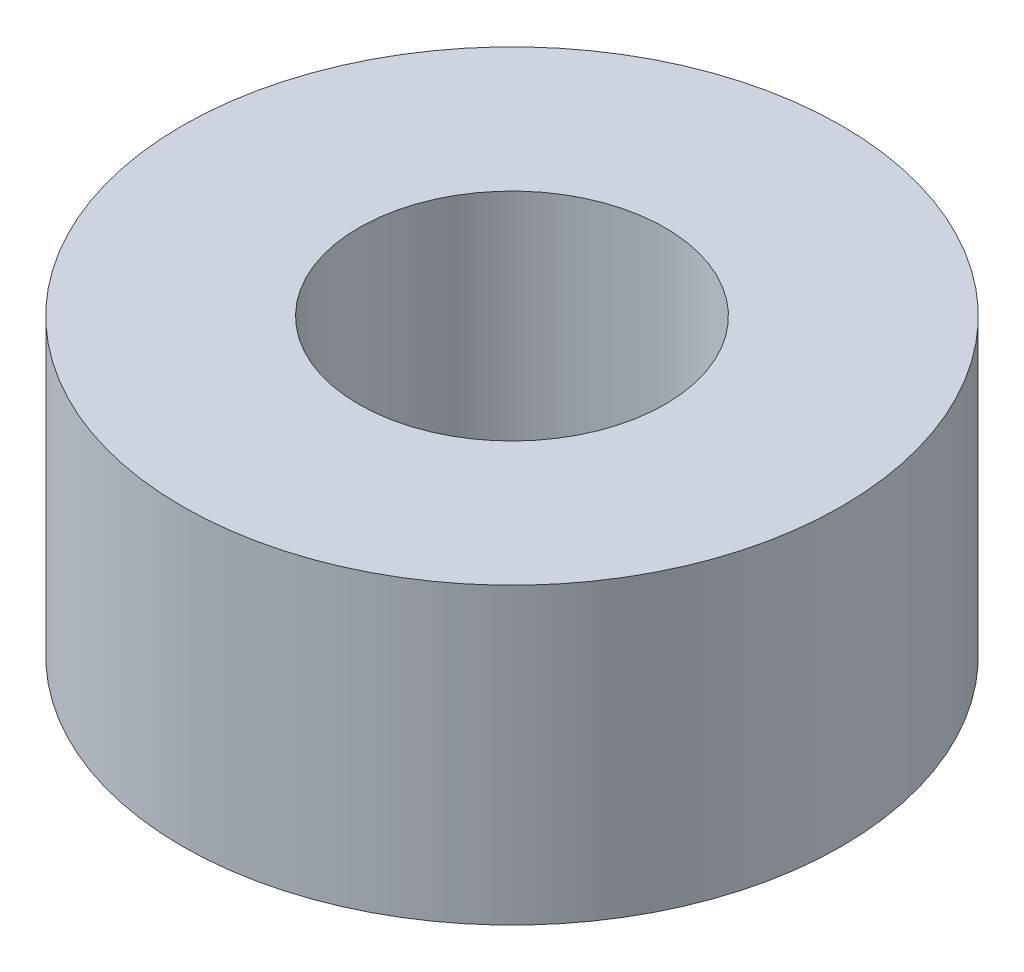
SolidWorks part; units mm, degrees
ref_plane "Front Plane" through (0, 0, 0) normal (0, 0, 1) x (1, 0, 0)
ref_plane "Top Plane" through (0, 0, 0) normal (0, 1, 0) x (1, 0, 0)
ref_plane "Right Plane" through (0, 0, 0) normal (1, 0, 0) x (0, 0, -1)
sketch "Sketch1" plane through (0, 0, 0) normal (0, 1, 0) x (1, 0, 0)
  circle A0 centre (0, 0) radius 5.6
  circle A1 centre (0, 0) radius 2.6
  dimension "D1" = 5.2
  dimension "D2" = 3
extrude "Boss-Extrude1" add sketch "Sketch1" along normal blind 5
